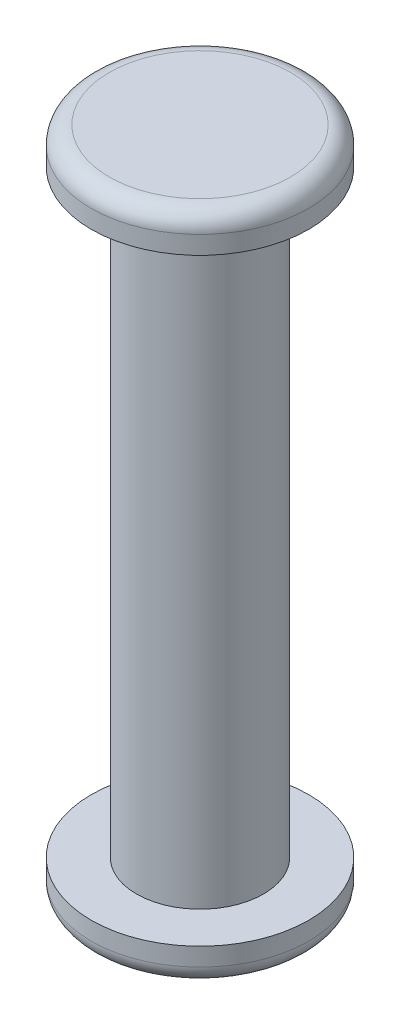
SolidWorks part; units mm, degrees
ref_plane "Front Plane" through (0, 0, 0) normal (0, 0, 1) x (1, 0, 0)
ref_plane "Top Plane" through (0, 0, 0) normal (0, 1, 0) x (1, 0, 0)
ref_plane "Right Plane" through (0, 0, 0) normal (1, 0, 0) x (0, 0, -1)
sketch "Sketch1" plane through (0, 0, 0) normal (0, 1, 0) x (1, 0, 0)
  circle A0 centre (0, 0) radius 1.75
  dimension "D1" = 3.5
extrude "Boss-Extrude1" add sketch "Sketch1" along normal blind 16.5
sketch "Sketch2" plane through (0, 0, 0) normal (0, 0, 1) x (1, 0, 0)
  line L0 (0, 0) -> (0, 16.5) construction
  line L1 (-1.75, 0) -> (1.75, 0) construction
  line L2 (1.75, 16.5) -> (-1.75, 16.5) construction
  line L3 (-7.3525, 8.25) -> (7.3525, 8.25) construction
  line L4 (0, 16.5) -> (-3, 16.5)
  line L5 (-3, 16.5) -> (-3, 17.5)
  line L6 (-3, 17.5) -> (0, 17.5)
  line L7 (0, 17.5) -> (0, 16.5)
  line L8 (-3, -1) -> (0, -1)
  line L9 (-3, 0) -> (-3, -1)
  line L10 (0, 0) -> (-3, 0)
  line L11 (0, -1) -> (0, 0)
  point P9 (0, 8.25)
  dimension "D1" = 1
  dimension "D2" = 3
revolve "Revolve1" add sketch "Sketch2" angle 360 about L0
fillet "Fillet1" radius 0.5 2 edges at (0, -1, -3) (0, 17.5, -3)
